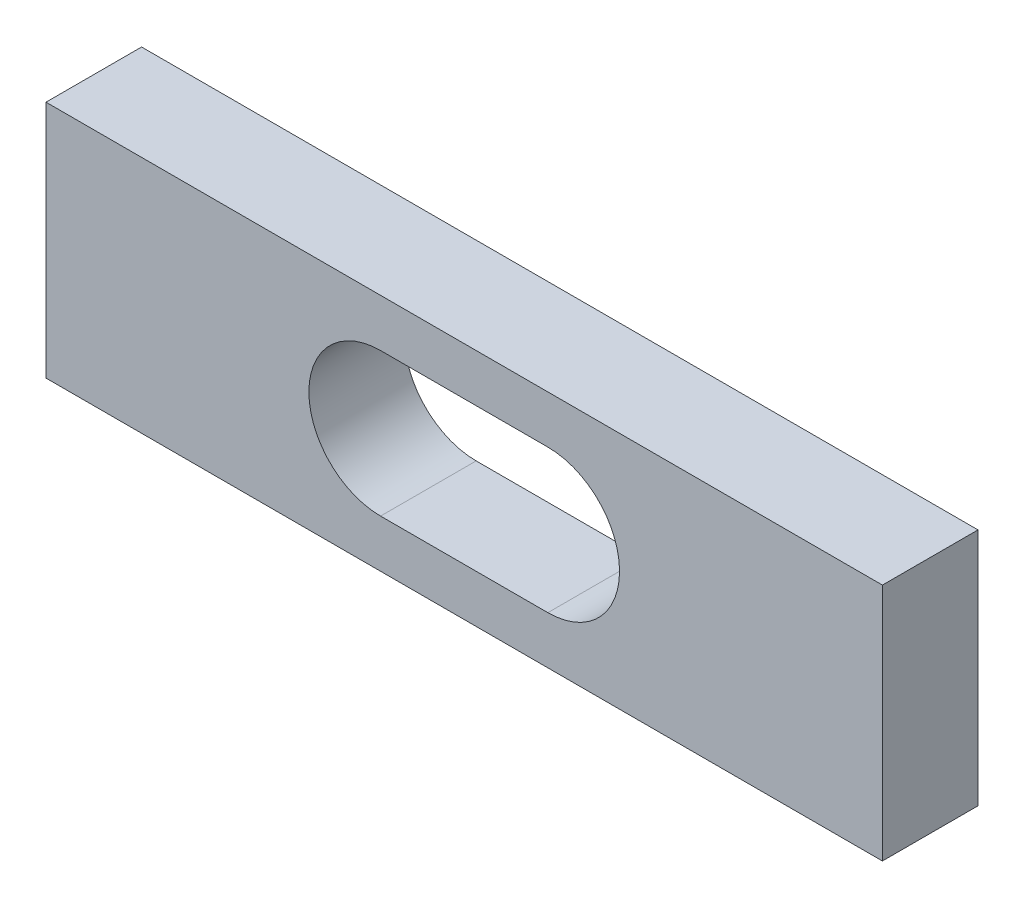
SolidWorks part; units mm, degrees
ref_plane "Alzado" through (0, 0, 0) normal (0, 0, 1) x (1, 0, 0)
ref_plane "Planta" through (0, 0, 0) normal (0, 1, 0) x (1, 0, 0)
ref_plane "Vista lateral" through (0, 0, 0) normal (1, 0, 0) x (0, 0, -1)
sketch "Croquis1" plane through (0, 0, 0) normal (0, 0, 1) x (1, 0, 0)
  line L0 (0, 0) -> (0, 10)
  line L1 (0, 0) -> (35, 0)
  line L2 (5.5, 5) -> (29.5, 5) construction
  line L3 (0, 10) -> (35, 10)
  line L4 (35, 0) -> (35, 10)
  line L5 (5.5, 5) -> (0, 5) construction
  line L6 (29.5, 5) -> (35, 5) construction
  line L7 (14, 5) -> (21, 5) construction
  line L8 (14, 8) -> (21, 8)
  line L9 (14, 2) -> (21, 2)
  circle A0 centre (29.5, 5) radius 2.5
  circle A1 centre (5.5, 5) radius 2.5
  arc A2 (14, 8) -> (14, 2) centre (14, 5) ccw
  arc A3 (21, 2) -> (21, 8) centre (21, 5) ccw
  point P5 (17.5, 5)
  point P18 (0, 0)
  point P19 (21.0652, 5)
  dimension "D3" = 5
  dimension "D4" = 24
  dimension "D1" = 35
  dimension "D2" = 5
  dimension "D5" = 5
  dimension "D6" = 3
  dimension "D7" = 7
extrude "Saliente-Extruir1" add sketch "Croquis1" along normal blind 2
sketch "Croquis2" plane through (0, 0, 2) normal (0, 0, 1) x (1, 0, 0)
  line L0 (14, 5) -> (21, 5) construction
  line L1 (0, 0) -> (35, 0)
  line L2 (0, 0) -> (0, 10)
  line L3 (0, 10) -> (35, 10)
  line L4 (35, 0) -> (35, 10)
  line L5 (14, 8) -> (21, 8)
  line L6 (14, 2) -> (21, 2)
  arc A0 (14, 8) -> (14, 2) centre (14, 5) ccw
  arc A1 (21, 2) -> (21, 8) centre (21, 5) ccw
  arc A2 (21, 2) -> (21, 8) centre (21, 5) ccw construction
  point P10 (17.5, 5)
extrude "Saliente-Extruir2" add sketch "Croquis2" along normal blind 2
